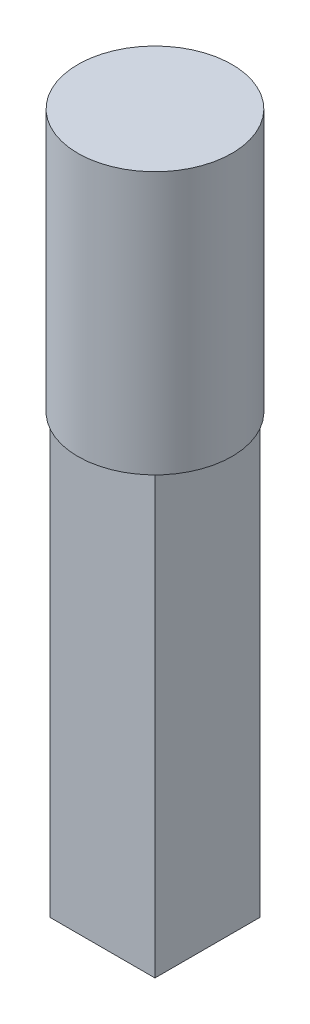
SolidWorks part; units mm, degrees
ref_plane "前视基准面" through (0, 0, 0) normal (0, 0, 1) x (1, 0, 0)
ref_plane "上视基准面" through (0, 0, 0) normal (0, 1, 0) x (1, 0, 0)
ref_plane "右视基准面" through (0, 0, 0) normal (1, 0, 0) x (0, 0, -1)
other "Configuration Table"
sketch "草图1" plane through (0, 0, 0) normal (0, 1, 0) x (1, 0, 0)
  line L1 (-30, 30) -> (30, 30)
  line L2 (-30, 30) -> (-30, -30)
  line L3 (-30, -30) -> (30, -30)
  line L4 (30, 30) -> (30, -30)
  line L5 (-30, 30) -> (30, -30) construction
  line L6 (-30, -30) -> (30, 30) construction
  point P0 (0, 0)
  dimension "D1" = 60
  dimension "D2" = 60
extrude "凸台-拉伸1" add sketch "草图1" along normal blind 250
sketch "草图2" plane through (0, 250, 0) normal (0, 1, 0) x (1, 0, 0)
  circle A0 centre (0, 0) radius 44
  dimension "D1" = 88
extrude "凸台-拉伸2" add sketch "草图2" along normal blind 150
